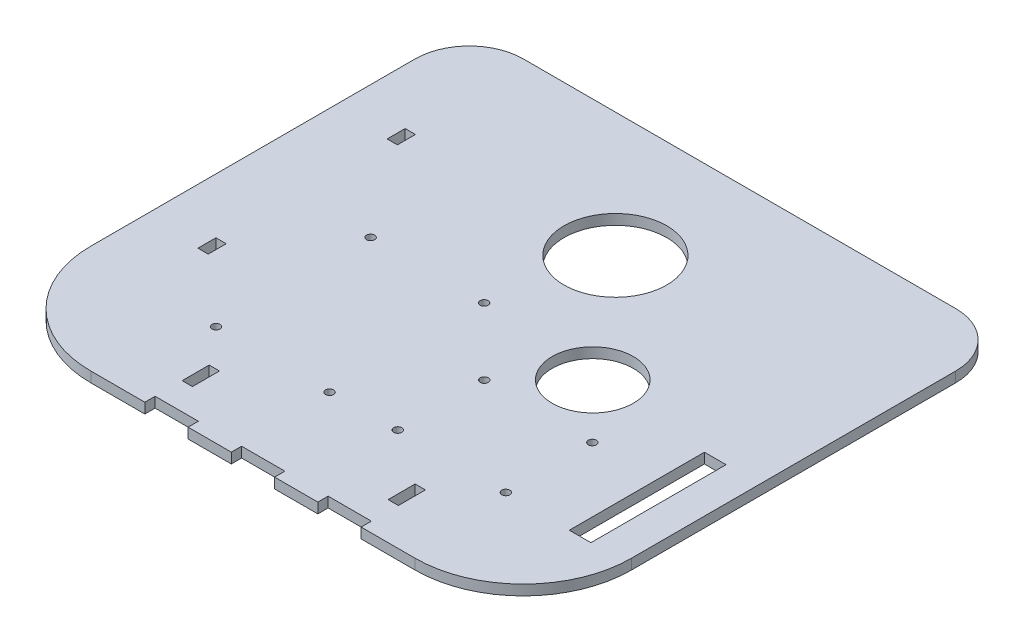
SolidWorks part; units mm, degrees
ref_plane "Front Plane" through (0, 0, 0) normal (0, 0, 1) x (1, 0, 0)
ref_plane "Top Plane" through (0, 0, 0) normal (0, 1, 0) x (1, 0, 0)
ref_plane "Right Plane" through (0, 0, 0) normal (1, 0, 0) x (0, 0, -1)
sketch "Sketch1" plane through (0, 0, 0) normal (0, 1, 0) x (1, 0, 0)
  line L1 (-127, 114.3) -> (127, 114.3)
  line L2 (-127, 114.3) -> (-127, -114.3)
  line L3 (-127, -114.3) -> (127, -114.3)
  line L4 (127, 114.3) -> (127, -114.3)
  line L5 (-127, 114.3) -> (127, -114.3) construction
  line L6 (-127, -114.3) -> (127, 114.3) construction
  point P0 (0, 0)
  dimension "D1" = 254
  dimension "D2" = 228.6
extrude "Boss-Extrude1" add sketch "Sketch1" along normal blind 4.826
sketch "Sketch4" plane through (0, 4.826, 0) normal (0, 1, 0) x (1, 0, 0)
  line L0 (0, -114.3) -> (0, 114.3) construction
  line L1 (-127, -114.3) -> (127, -114.3) construction
  line L2 (127, 114.3) -> (-127, 114.3) construction
  line L3 (-127, 88.9) -> (-101.6, 88.9) construction
  line L4 (-127, 114.3) -> (-127, -114.3) construction
  line L5 (-101.6, 88.9) -> (-101.6, 114.3) construction
  line L6 (-127, 88.9) -> (-127, 114.3)
  line L7 (-127, 114.3) -> (-101.6, 114.3)
  line L8 (127, 88.9) -> (127, 114.3)
  line L9 (127, 114.3) -> (101.6, 114.3)
  arc A0 (-127, 88.9) -> (-101.6, 114.3) centre (-101.6, 88.9) cw
  arc A1 (127, 88.9) -> (101.6, 114.3) centre (101.6, 88.9) ccw
  dimension "D1" = 25.4
  dimension "D2" = 25.4
extrude "Cut-Extrude3" cut sketch "Sketch4" against normal blind 4.826
sketch "Sketch19" plane through (0, 4.826, 0) normal (0, 1, 0) x (1, 0, 0)
  line L0 (-101, -39.1583) -> (-101, -30.6917) construction
  line L1 (-101, -39.1583) -> (-96.174, -39.1583) construction
  line L2 (-96.174, -39.1583) -> (-96.174, -30.6917) construction
  line L3 (-101, -30.6917) -> (-96.174, -30.6917) construction
  line L4 (-101, 49.7417) -> (-101, 58.2083) construction
  line L5 (-101, 49.7417) -> (-96.174, 49.7417) construction
  line L6 (-96.174, 49.7417) -> (-96.174, 58.2083) construction
  line L7 (-101, 58.2083) -> (-96.174, 58.2083) construction
  line L8 (-101, -39.1583) -> (-101, -30.6917)
  line L9 (-101, -39.1583) -> (-96.174, -39.1583)
  line L10 (-96.174, -39.1583) -> (-96.174, -30.6917)
  line L11 (-101, -30.6917) -> (-96.174, -30.6917)
  line L12 (-101, 49.7417) -> (-101, 58.2083)
  line L13 (-101, 49.7417) -> (-96.174, 49.7417)
  line L14 (-96.174, 49.7417) -> (-96.174, 58.2083)
  line L15 (-101, 58.2083) -> (-96.174, 58.2083)
extrude "Cut-Extrude16" cut sketch "Sketch19" against normal through all
fillet "Fillet11" radius 50.8 2 edges at (-127, 2.413, 114.3) (127, 2.413, 114.3)
sketch "Sketch20" plane through (0, 0, 0) normal (0, -1, 0) x (1, 0, 0)
  line L1 (101, 66.675) -> (111.16, 66.675)
  line L2 (101, 66.675) -> (101, 3.175)
  line L3 (101, 3.175) -> (111.16, 3.175)
  line L4 (111.16, 66.675) -> (111.16, 3.175)
  dimension "D1" = 10.16
extrude "Cut-Extrude17" cut sketch "Sketch20" against normal through all
sketch "Sketch23" plane through (0, 4.826, 0) normal (0, 1, 0) x (1, 0, 0)
  circle A0 centre (70.7411, -25.5764) radius 1.905 construction
  circle A1 centre (70.7411, -66.2164) radius 1.905 construction
  circle A2 centre (19.9411, -25.5764) radius 1.905 construction
  circle A3 centre (19.9411, -66.2164) radius 1.905 construction
  circle A4 centre (-11.4804, 5.7926) radius 1.905 construction
  circle A5 centre (-64.8204, 5.7926) radius 1.905 construction
  circle A6 centre (-64.8204, -66.8514) radius 1.905 construction
  circle A7 centre (-11.4804, -66.8514) radius 1.905 construction
  circle A8 centre (70.7411, -25.5764) radius 1.905
  circle A9 centre (70.7411, -66.2164) radius 1.905
  circle A10 centre (19.9411, -25.5764) radius 1.905
  circle A11 centre (19.9411, -66.2164) radius 1.905
  circle A12 centre (-11.4804, 5.7926) radius 1.905
  circle A13 centre (-64.8204, 5.7926) radius 1.905
  circle A14 centre (-64.8204, -66.8514) radius 1.905
  circle A15 centre (-11.4804, -66.8514) radius 1.905
extrude "Cut-Extrude18" cut sketch "Sketch23" against normal through all
sketch "Sketch24" plane through (0, 0, 0) normal (0, -1, 0) x (1, 0, 0)
  line L0 (50.8, 114.3) -> (50.8, 109.474) construction
  line L1 (50.8, 114.3) -> (50.8, 109.474)
  line L2 (50.8, 114.3) -> (50.8, 109.474)
  line L3 (30.48, 114.3) -> (50.8, 114.3) construction
  line L4 (30.48, 109.474) -> (50.8, 109.474) construction
  line L5 (30.48, 114.3) -> (30.48, 109.474) construction
  line L6 (10.16, 114.3) -> (10.16, 109.474) construction
  line L7 (-10.16, 109.474) -> (10.16, 109.474) construction
  line L8 (-10.16, 114.3) -> (-10.16, 109.474) construction
  line L9 (-10.16, 114.3) -> (10.16, 114.3) construction
  line L10 (-30.48, 114.3) -> (-30.48, 109.474) construction
  line L11 (-50.8, 114.3) -> (-30.48, 114.3) construction
  line L12 (-50.8, 114.3) -> (-50.8, 109.474) construction
  line L13 (-50.8, 109.474) -> (-30.48, 109.474) construction
  line L14 (30.48, 114.3) -> (50.8, 114.3)
  line L15 (50.8, 114.3) -> (50.8, 109.474)
  line L16 (30.48, 109.474) -> (50.8, 109.474)
  line L17 (30.48, 114.3) -> (30.48, 109.474)
  line L18 (10.16, 114.3) -> (10.16, 109.474)
  line L19 (-10.16, 109.474) -> (10.16, 109.474)
  line L20 (-10.16, 114.3) -> (-10.16, 109.474)
  line L21 (-10.16, 114.3) -> (10.16, 114.3)
  line L22 (-30.48, 114.3) -> (-30.48, 109.474)
  line L23 (-50.8, 114.3) -> (-30.48, 114.3)
  line L24 (-50.8, 114.3) -> (-50.8, 109.474)
  line L25 (-50.8, 109.474) -> (-30.48, 109.474)
  line M21 (76.2, 114.3) -> (-76.2, 114.3)
extrude "Cut-Extrude19" cut sketch "Sketch24" against normal through all contours L17 L16 L1 M21 | L24 L25 L22 M21 | L21 L18 L19 L20
sketch "Sketch26" plane through (0, 0, 0) normal (0, -1, 0) x (1, 0, 0)
  circle A0 centre (0, -55.982) radius 24.13 construction
  circle A1 centre (0, -55.982) radius 24.13
extrude "Cut-Extrude20" cut sketch "Sketch26" against normal through all
sketch "Sketch27" plane through (0, 0, 0) normal (0, -1, 0) x (1, 0, 0)
  line L0 (-45.974, 84.074) -> (-45.974, 96.774) construction
  line L1 (-50.8, 96.774) -> (-45.974, 96.774) construction
  line L2 (-50.8, 84.074) -> (-50.8, 96.774) construction
  line L3 (-50.8, 84.074) -> (-45.974, 84.074) construction
  line L4 (50.8, 84.074) -> (50.8, 96.774) construction
  line L5 (50.8, 84.074) -> (45.974, 84.074) construction
  line L6 (45.974, 84.074) -> (45.974, 96.774) construction
  line L7 (50.8, 96.774) -> (45.974, 96.774) construction
  line L8 (-45.974, 84.074) -> (-45.974, 96.774)
  line L9 (-50.8, 96.774) -> (-45.974, 96.774)
  line L10 (-50.8, 84.074) -> (-50.8, 96.774)
  line L11 (-50.8, 84.074) -> (-45.974, 84.074)
  line L12 (50.8, 84.074) -> (50.8, 96.774)
  line L13 (50.8, 84.074) -> (45.974, 84.074)
  line L14 (45.974, 84.074) -> (45.974, 96.774)
  line L15 (50.8, 96.774) -> (45.974, 96.774)
extrude "Cut-Extrude21" cut sketch "Sketch27" against normal through all
sketch "Sketch28" plane through (0, 4.826, 0) normal (0, 1, 0) x (1, 0, 0)
  line L0 (75.3131, -20.4964) -> (75.3131, -71.2964) construction
  circle A0 centre (45.3411, 0) radius 19.05
  dimension "D1" = 38.1
  dimension "D2" = 29.972
extrude "Cut-Extrude22" cut sketch "Sketch28" against normal through all
equation "\"MDF\"= 0.19in"
equation "\"GenDiameter\"= 60mm"
equation "\"GenCutDiameter\" = 1.8in"
equation "\"GenCutDistance\" = 1"
equation "\"TowerHeight\" = 6in"
equation "\"TowerFrontBase\" = 3in"
equation "\"FunnelHeight\" = 1in"
equation "\"FunnelAngle\" = 20"
equation "\"TowerSideBase\" = 3in"
equation "\"BaseLength\" = 9in"
equation "\"BaseWidth\" = 10in"
equation "\"WheelHoleLength\" = 3.25in"
equation "\"WheelHoleWidth\" = 26mm"
equation "\"DropLength\" = 1in"
equation "\"D1@Sketch1\"=\"BaseWidth\""
equation "\"D2@Sketch1\"=\"BaseLength\""
equation "\"D1@Boss-Extrude1\"=\"MDF\""
equation "\"WheelHoleFromBack\" = 1.5in"
equation "\"DropWidth\" = 8.5in"
equation "\"BumperWidth\" = 2in"
equation "\"D1@Cut-Extrude3\"=\"MDF\""
equation "\"DropWidthTop\" = 0in"
